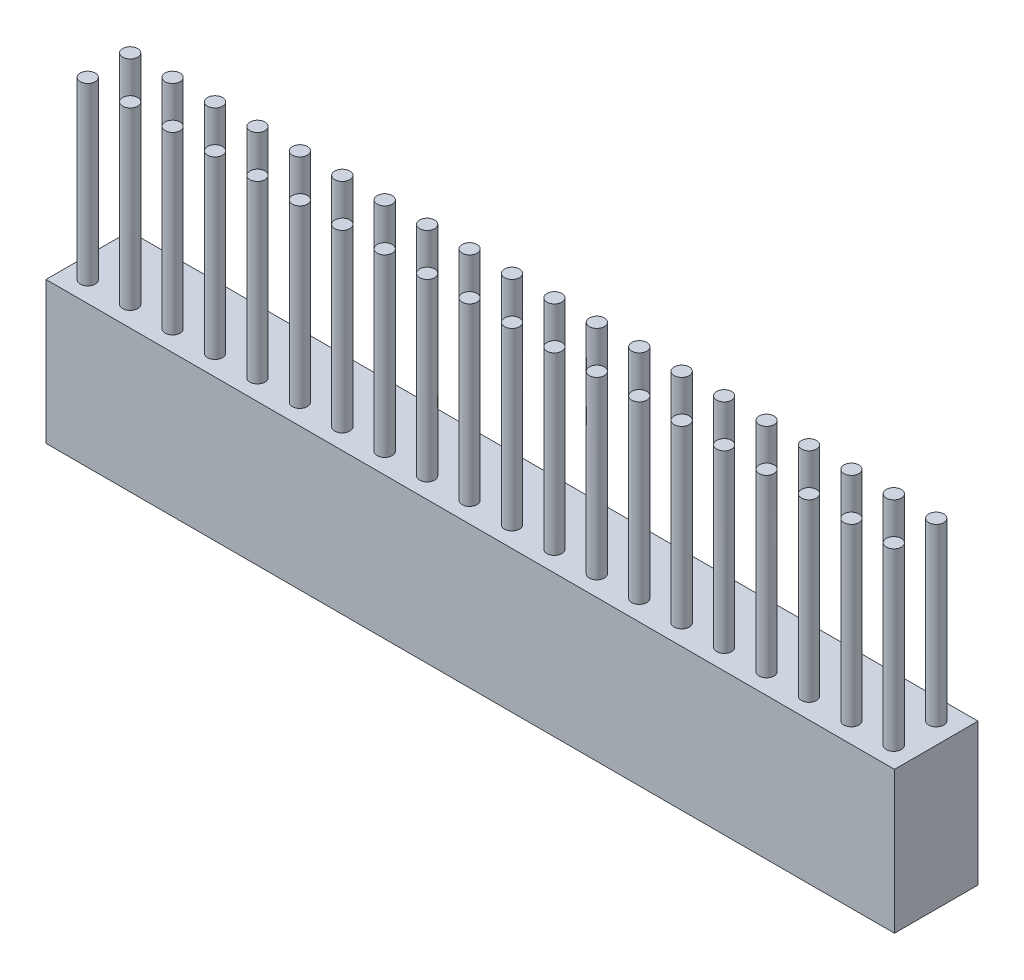
SolidWorks part; units mm, degrees
ref_plane "Front Plane" through (0, 0, 0) normal (0, 0, 1) x (1, 0, 0)
ref_plane "Top Plane" through (0, 0, 0) normal (0, 1, 0) x (1, 0, 0)
ref_plane "Right Plane" through (0, 0, 0) normal (1, 0, 0) x (0, 0, -1)
sketch "Sketch1" plane through (0, 0, 0) normal (0, 1, 0) x (1, 0, 0)
  line L1 (-25.4, -2.5) -> (25.4, -2.5)
  line L2 (-25.4, -2.5) -> (-25.4, 2.5)
  line L3 (-25.4, 2.5) -> (25.4, 2.5)
  line L4 (25.4, -2.5) -> (25.4, 2.5)
  line L5 (-25.4, -2.5) -> (25.4, 2.5) construction
  line L6 (-25.4, 2.5) -> (25.4, -2.5) construction
  point P0 (0, 0)
  dimension "D1" = 50.8
  dimension "D2" = 5
extrude "Boss-Extrude1" add sketch "Sketch1" along normal blind 8.5
sketch "Sketch2" plane through (0, 8.5, 0) normal (0, 1, 0) x (1, 0, 0)
  line L0 (-0.4416, 0) -> (-41.0203, 0) construction
  line L1 (-25.4, 2.5) -> (-25.4, -2.5) construction
  circle A0 centre (-24.13, 1.27) radius 0.4498
  circle A1 centre (-21.59, 1.27) radius 0.4498
  circle A2 centre (-19.05, 1.27) radius 0.4498
  circle A3 centre (-16.51, 1.27) radius 0.4498
  circle A4 centre (-13.97, 1.27) radius 0.4498
  circle A5 centre (-11.43, 1.27) radius 0.4498
  circle A6 centre (-8.89, 1.27) radius 0.4498
  circle A7 centre (-6.35, 1.27) radius 0.4498
  circle A8 centre (-3.81, 1.27) radius 0.4498
  circle A9 centre (-1.27, 1.27) radius 0.4498
  circle A10 centre (1.27, 1.27) radius 0.4498
  circle A11 centre (3.81, 1.27) radius 0.4498
  circle A12 centre (6.35, 1.27) radius 0.4498
  circle A13 centre (8.89, 1.27) radius 0.4498
  circle A14 centre (11.43, 1.27) radius 0.4498
  circle A15 centre (13.97, 1.27) radius 0.4498
  circle A16 centre (16.51, 1.27) radius 0.4498
  circle A17 centre (19.05, 1.27) radius 0.4498
  circle A18 centre (21.59, 1.27) radius 0.4498
  circle A19 centre (24.13, 1.27) radius 0.4498
  circle A20 centre (-21.59, -1.27) radius 0.4498
  circle A21 centre (-19.05, -1.27) radius 0.4498
  circle A22 centre (-16.51, -1.27) radius 0.4498
  circle A23 centre (-13.97, -1.27) radius 0.4498
  circle A24 centre (-11.43, -1.27) radius 0.4498
  circle A25 centre (-8.89, -1.27) radius 0.4498
  circle A26 centre (-6.35, -1.27) radius 0.4498
  circle A27 centre (-3.81, -1.27) radius 0.4498
  circle A28 centre (-1.27, -1.27) radius 0.4498
  circle A29 centre (1.27, -1.27) radius 0.4498
  circle A30 centre (3.81, -1.27) radius 0.4498
  circle A31 centre (6.35, -1.27) radius 0.4498
  circle A32 centre (8.89, -1.27) radius 0.4498
  circle A33 centre (11.43, -1.27) radius 0.4498
  circle A34 centre (13.97, -1.27) radius 0.4498
  circle A35 centre (16.51, -1.27) radius 0.4498
  circle A36 centre (19.05, -1.27) radius 0.4498
  circle A37 centre (21.59, -1.27) radius 0.4498
  circle A38 centre (24.13, -1.27) radius 0.4498
  circle A39 centre (-24.13, -1.27) radius 0.4498
  dimension "D1" = 1.27
  dimension "D2" = 1.27
  dimension "D3" = 20
  dimension "D4" = 2
extrude "Boss-Extrude2" add sketch "Sketch2" along normal blind 10.5
sketch "Sketch3" plane through (0, 0, 0) normal (0, -1, 0) x (1, 0, 0)
  line L0 (0, 0.0101) -> (6.495, 0.0101) construction
  line L1 (-25.4, -2.5) -> (-25.4, 2.5) construction
  line L2 (-23.495, 0.6451) -> (-24.765, 0.6451)
  line L3 (-23.495, 0.6451) -> (-23.495, 1.9151)
  line L4 (-23.495, 1.9151) -> (-24.765, 1.9151)
  line L5 (-24.765, 0.6451) -> (-24.765, 1.9151)
  line L6 (-23.495, 0.6451) -> (-24.765, 1.9151) construction
  line L7 (-23.495, 1.9151) -> (-24.765, 0.6451) construction
  line L8 (-20.955, 0.6451) -> (-22.225, 0.6451)
  line L9 (-20.955, 0.6451) -> (-20.955, 1.9151)
  line L10 (-20.955, 1.9151) -> (-22.225, 1.9151)
  line L11 (-22.225, 0.6451) -> (-22.225, 1.9151)
  line L12 (-18.415, 0.6451) -> (-19.685, 0.6451)
  line L13 (-18.415, 0.6451) -> (-18.415, 1.9151)
  line L14 (-18.415, 1.9151) -> (-19.685, 1.9151)
  line L15 (-19.685, 0.6451) -> (-19.685, 1.9151)
  line L16 (-15.875, 0.6451) -> (-17.145, 0.6451)
  line L17 (-15.875, 0.6451) -> (-15.875, 1.9151)
  line L18 (-15.875, 1.9151) -> (-17.145, 1.9151)
  line L19 (-17.145, 0.6451) -> (-17.145, 1.9151)
  line L20 (-13.335, 0.6451) -> (-14.605, 0.6451)
  line L21 (-13.335, 0.6451) -> (-13.335, 1.9151)
  line L22 (-13.335, 1.9151) -> (-14.605, 1.9151)
  line L23 (-14.605, 0.6451) -> (-14.605, 1.9151)
  line L24 (-10.795, 0.6451) -> (-12.065, 0.6451)
  line L25 (-10.795, 0.6451) -> (-10.795, 1.9151)
  line L26 (-10.795, 1.9151) -> (-12.065, 1.9151)
  line L27 (-12.065, 0.6451) -> (-12.065, 1.9151)
  line L28 (-8.255, 0.6451) -> (-9.525, 0.6451)
  line L29 (-8.255, 0.6451) -> (-8.255, 1.9151)
  line L30 (-8.255, 1.9151) -> (-9.525, 1.9151)
  line L31 (-9.525, 0.6451) -> (-9.525, 1.9151)
  line L32 (-5.715, 0.6451) -> (-6.985, 0.6451)
  line L33 (-5.715, 0.6451) -> (-5.715, 1.9151)
  line L34 (-5.715, 1.9151) -> (-6.985, 1.9151)
  line L35 (-6.985, 0.6451) -> (-6.985, 1.9151)
  line L36 (-3.175, 0.6451) -> (-4.445, 0.6451)
  line L37 (-3.175, 0.6451) -> (-3.175, 1.9151)
  line L38 (-3.175, 1.9151) -> (-4.445, 1.9151)
  line L39 (-4.445, 0.6451) -> (-4.445, 1.9151)
  line L40 (-0.635, 0.6451) -> (-1.905, 0.6451)
  line L41 (-0.635, 0.6451) -> (-0.635, 1.9151)
  line L42 (-0.635, 1.9151) -> (-1.905, 1.9151)
  line L43 (-1.905, 0.6451) -> (-1.905, 1.9151)
  line L44 (1.905, 0.6451) -> (0.635, 0.6451)
  line L45 (1.905, 0.6451) -> (1.905, 1.9151)
  line L46 (1.905, 1.9151) -> (0.635, 1.9151)
  line L47 (0.635, 0.6451) -> (0.635, 1.9151)
  line L48 (4.445, 0.6451) -> (3.175, 0.6451)
  line L49 (4.445, 0.6451) -> (4.445, 1.9151)
  line L50 (4.445, 1.9151) -> (3.175, 1.9151)
  line L51 (3.175, 0.6451) -> (3.175, 1.9151)
  line L52 (6.985, 0.6451) -> (5.715, 0.6451)
  line L53 (6.985, 0.6451) -> (6.985, 1.9151)
  line L54 (6.985, 1.9151) -> (5.715, 1.9151)
  line L55 (5.715, 0.6451) -> (5.715, 1.9151)
  line L56 (9.525, 0.6451) -> (8.255, 0.6451)
  line L57 (9.525, 0.6451) -> (9.525, 1.9151)
  line L58 (9.525, 1.9151) -> (8.255, 1.9151)
  line L59 (8.255, 0.6451) -> (8.255, 1.9151)
  line L60 (12.065, 0.6451) -> (10.795, 0.6451)
  line L61 (12.065, 0.6451) -> (12.065, 1.9151)
  line L62 (12.065, 1.9151) -> (10.795, 1.9151)
  line L63 (10.795, 0.6451) -> (10.795, 1.9151)
  line L64 (14.605, 0.6451) -> (13.335, 0.6451)
  line L65 (14.605, 0.6451) -> (14.605, 1.9151)
  line L66 (14.605, 1.9151) -> (13.335, 1.9151)
  line L67 (13.335, 0.6451) -> (13.335, 1.9151)
  line L68 (17.145, 0.6451) -> (15.875, 0.6451)
  line L69 (17.145, 0.6451) -> (17.145, 1.9151)
  line L70 (17.145, 1.9151) -> (15.875, 1.9151)
  line L71 (15.875, 0.6451) -> (15.875, 1.9151)
  line L72 (19.685, 0.6451) -> (18.415, 0.6451)
  line L73 (19.685, 0.6451) -> (19.685, 1.9151)
  line L74 (19.685, 1.9151) -> (18.415, 1.9151)
  line L75 (18.415, 0.6451) -> (18.415, 1.9151)
  line L76 (22.225, 0.6451) -> (20.955, 0.6451)
  line L77 (22.225, 0.6451) -> (22.225, 1.9151)
  line L78 (22.225, 1.9151) -> (20.955, 1.9151)
  line L79 (20.955, 0.6451) -> (20.955, 1.9151)
  line L80 (24.765, 0.6451) -> (23.495, 0.6451)
  line L81 (24.765, 0.6451) -> (24.765, 1.9151)
  line L82 (24.765, 1.9151) -> (23.495, 1.9151)
  line L83 (23.495, 0.6451) -> (23.495, 1.9151)
  line L84 (-20.955, -1.8949) -> (-22.225, -1.8949)
  line L85 (-20.955, -1.8949) -> (-20.955, -0.6249)
  line L86 (-20.955, -0.6249) -> (-22.225, -0.6249)
  line L87 (-22.225, -1.8949) -> (-22.225, -0.6249)
  line L88 (-18.415, -1.8949) -> (-19.685, -1.8949)
  line L89 (-18.415, -1.8949) -> (-18.415, -0.6249)
  line L90 (-18.415, -0.6249) -> (-19.685, -0.6249)
  line L91 (-19.685, -1.8949) -> (-19.685, -0.6249)
  line L92 (-15.875, -1.8949) -> (-17.145, -1.8949)
  line L93 (-15.875, -1.8949) -> (-15.875, -0.6249)
  line L94 (-15.875, -0.6249) -> (-17.145, -0.6249)
  line L95 (-17.145, -1.8949) -> (-17.145, -0.6249)
  line L96 (-13.335, -1.8949) -> (-14.605, -1.8949)
  line L97 (-13.335, -1.8949) -> (-13.335, -0.6249)
  line L98 (-13.335, -0.6249) -> (-14.605, -0.6249)
  line L99 (-14.605, -1.8949) -> (-14.605, -0.6249)
  line L100 (-10.795, -1.8949) -> (-12.065, -1.8949)
  line L101 (-10.795, -1.8949) -> (-10.795, -0.6249)
  line L102 (-10.795, -0.6249) -> (-12.065, -0.6249)
  line L103 (-12.065, -1.8949) -> (-12.065, -0.6249)
  line L104 (-8.255, -1.8949) -> (-9.525, -1.8949)
  line L105 (-8.255, -1.8949) -> (-8.255, -0.6249)
  line L106 (-8.255, -0.6249) -> (-9.525, -0.6249)
  line L107 (-9.525, -1.8949) -> (-9.525, -0.6249)
  line L108 (-5.715, -1.8949) -> (-6.985, -1.8949)
  line L109 (-5.715, -1.8949) -> (-5.715, -0.6249)
  line L110 (-5.715, -0.6249) -> (-6.985, -0.6249)
  line L111 (-6.985, -1.8949) -> (-6.985, -0.6249)
  line L112 (-3.175, -1.8949) -> (-4.445, -1.8949)
  line L113 (-3.175, -1.8949) -> (-3.175, -0.6249)
  line L114 (-3.175, -0.6249) -> (-4.445, -0.6249)
  line L115 (-4.445, -1.8949) -> (-4.445, -0.6249)
  line L116 (-0.635, -1.8949) -> (-1.905, -1.8949)
  line L117 (-0.635, -1.8949) -> (-0.635, -0.6249)
  line L118 (-0.635, -0.6249) -> (-1.905, -0.6249)
  line L119 (-1.905, -1.8949) -> (-1.905, -0.6249)
  line L120 (1.905, -1.8949) -> (0.635, -1.8949)
  line L121 (1.905, -1.8949) -> (1.905, -0.6249)
  line L122 (1.905, -0.6249) -> (0.635, -0.6249)
  line L123 (0.635, -1.8949) -> (0.635, -0.6249)
  line L124 (4.445, -1.8949) -> (3.175, -1.8949)
  line L125 (4.445, -1.8949) -> (4.445, -0.6249)
  line L126 (4.445, -0.6249) -> (3.175, -0.6249)
  line L127 (3.175, -1.8949) -> (3.175, -0.6249)
  line L128 (6.985, -1.8949) -> (5.715, -1.8949)
  line L129 (6.985, -1.8949) -> (6.985, -0.6249)
  line L130 (6.985, -0.6249) -> (5.715, -0.6249)
  line L131 (5.715, -1.8949) -> (5.715, -0.6249)
  line L132 (9.525, -1.8949) -> (8.255, -1.8949)
  line L133 (9.525, -1.8949) -> (9.525, -0.6249)
  line L134 (9.525, -0.6249) -> (8.255, -0.6249)
  line L135 (8.255, -1.8949) -> (8.255, -0.6249)
  line L136 (12.065, -1.8949) -> (10.795, -1.8949)
  line L137 (12.065, -1.8949) -> (12.065, -0.6249)
  line L138 (12.065, -0.6249) -> (10.795, -0.6249)
  line L139 (10.795, -1.8949) -> (10.795, -0.6249)
  line L140 (14.605, -1.8949) -> (13.335, -1.8949)
  line L141 (14.605, -1.8949) -> (14.605, -0.6249)
  line L142 (14.605, -0.6249) -> (13.335, -0.6249)
  line L143 (13.335, -1.8949) -> (13.335, -0.6249)
  line L144 (17.145, -1.8949) -> (15.875, -1.8949)
  line L145 (17.145, -1.8949) -> (17.145, -0.6249)
  line L146 (17.145, -0.6249) -> (15.875, -0.6249)
  line L147 (15.875, -1.8949) -> (15.875, -0.6249)
  line L148 (19.685, -1.8949) -> (18.415, -1.8949)
  line L149 (19.685, -1.8949) -> (19.685, -0.6249)
  line L150 (19.685, -0.6249) -> (18.415, -0.6249)
  line L151 (18.415, -1.8949) -> (18.415, -0.6249)
  line L152 (22.225, -1.8949) -> (20.955, -1.8949)
  line L153 (22.225, -1.8949) -> (22.225, -0.6249)
  line L154 (22.225, -0.6249) -> (20.955, -0.6249)
  line L155 (20.955, -1.8949) -> (20.955, -0.6249)
  line L156 (24.765, -1.8949) -> (23.495, -1.8949)
  line L157 (24.765, -1.8949) -> (24.765, -0.6249)
  line L158 (24.765, -0.6249) -> (23.495, -0.6249)
  line L159 (23.495, -1.8949) -> (23.495, -0.6249)
  line L160 (-23.495, -1.8949) -> (-24.765, -1.8949)
  line L161 (-23.495, -1.8949) -> (-23.495, -0.6249)
  line L162 (-23.495, -0.6249) -> (-24.765, -0.6249)
  line L163 (-24.765, -1.8949) -> (-24.765, -0.6249)
  point P1 (-24.13, 1.2801)
  dimension "D1" = 1.27
  dimension "D2" = 1.27
  dimension "D3" = 1.27
  dimension "D4" = 1.27
  dimension "D5" = 20
  dimension "D6" = 2
extrude "Cut-Extrude1" cut sketch "Sketch3" against normal blind 5
